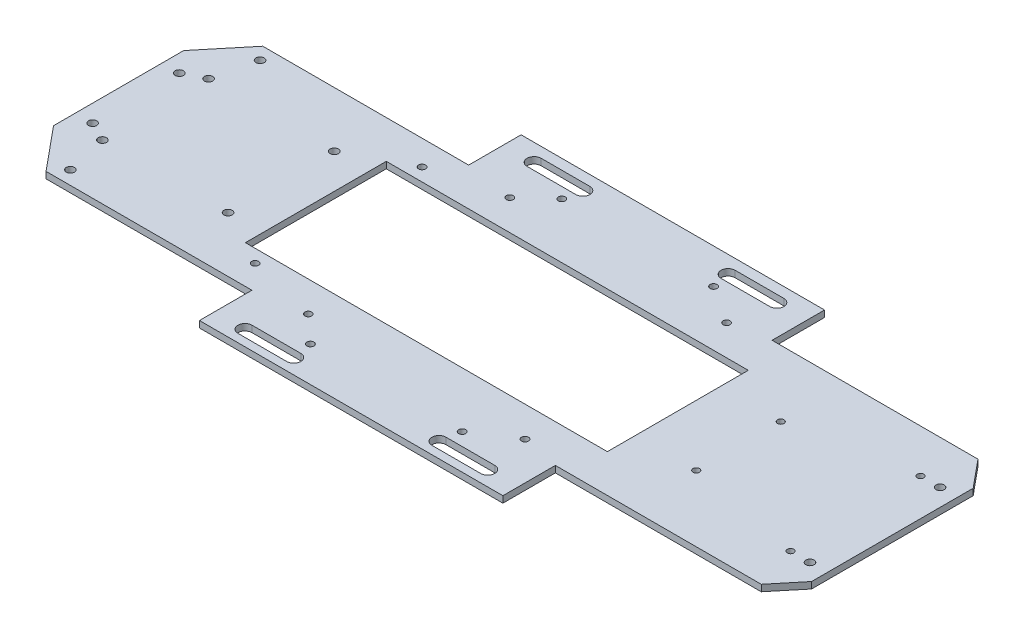
SolidWorks part; units mm, degrees
material "Perspex (TM) GS Acrylic Cast Sheet"
ref_plane "Front Plane" through (0, 0, 0) normal (0, 0, 1) x (1, 0, 0)
ref_plane "Top Plane" through (0, 0, 0) normal (0, 1, 0) x (1, 0, 0)
ref_plane "Right Plane" through (0, 0, 0) normal (1, 0, 0) x (0, 0, -1)
sketch "Sketch1" plane through (0, 0, 0) normal (0, 1, 0) x (1, 0, 0)
  line L0 (181.5, -30) -> (165, -50)
  line L1 (-165, -50) -> (-70, -50)
  line L3 (-165, 50) -> (-70, 50)
  line L4 (181.5, -30) -> (181.5, 30)
  line L5 (-181.5, 0) -> (181.5, 0) construction
  line L6 (0, 50) -> (0, -50) construction
  line L7 (181.5, 30) -> (165, 50)
  line L8 (-165, 50) -> (-181.5, 30)
  line L9 (-181.5, 30) -> (-181.5, -30)
  line L10 (-181.5, -30) -> (-165, -50)
  line L11 (70, 50) -> (165, 50)
  line L13 (-70, 50) -> (-70, 74.2)
  line L14 (-70, 74.2) -> (70, 74.2)
  line L15 (70, 50) -> (70, 74.2)
  line L17 (-70, -50) -> (-70, -74.2)
  line L18 (-70, -74.2) -> (70, -74.2)
  line L19 (70, -50) -> (70, -74.2)
  line L20 (70, -50) -> (165, -50)
  line L21 (0, 74.2) -> (0, -74.2) construction
  line L22 (-90.5, 32.5) -> (76.5, 32.5)
  line L23 (-90.5, 32.5) -> (-90.5, -32.5)
  line L24 (-90.5, -32.5) -> (76.5, -32.5)
  line L25 (76.5, 32.5) -> (76.5, -32.5)
  line L26 (-70, 58) -> (70, 58) construction
  line L27 (-47.5, 46.5) -> (52.5, 46.5) construction
  line L28 (-47.5, -46.5) -> (52.5, -46.5) construction
  circle A0 centre (-35, -58) radius 1.6
  circle A2 centre (-35, 58) radius 1.6
  circle A3 centre (35, 58) radius 1.6
  circle A4 centre (35, -58) radius 1.6
  circle A5 centre (-80, 38.5) radius 1.6
  circle A6 centre (-80, -38.5) radius 1.6
  circle A7 centre (-47.5, 46.5) radius 1.6
  circle A8 centre (52.5, 46.5) radius 1.6
  circle A9 centre (52.5, -46.5) radius 1.6
  circle A10 centre (-47.5, -46.5) radius 1.6
  point P0 (0, 0)
  point P16 (0, 0)
  point P27 (76.5, 0)
  point P33 (0, 58)
  point P36 (0, -62.18)
  dimension "D15" = 3.2
  dimension "D16" = 3.2
  dimension "D21" = 3.2
  dimension "D22" = 3.2
  dimension "D26" = 3.2
  dimension "D27" = 3.2
  dimension "D30" = 3.2
  dimension "D1" = 100
  dimension "D3" = 16.5
  dimension "D2" = 363
  dimension "D5" = 20
  dimension "D6" = 20
  dimension "D4" = 330
  dimension "D7" = 140
  dimension "D8" = 24.2
  dimension "D10" = 65
  dimension "D11" = 167
  dimension "D9" = 111.5
  dimension "D12" = 16.2
  dimension "D13" = 35
  dimension "D14" = 35
  dimension "D17" = 16.2
  dimension "D19" = 35
  dimension "D18" = 35
  dimension "D20" = 16.2
  dimension "D23" = 105
  dimension "D24" = 6
  dimension "D25" = 10
  dimension "D28" = 6
  dimension "D29" = 10
  dimension "D31" = 100
  dimension "D33" = 14
  dimension "D32" = 17.5
  dimension "D34" = 14
extrude "Boss-Extrude1" add sketch "Sketch1" along normal blind 3
sketch "Sketch2" plane through (0, 3, 0) normal (0, 1, 0) x (1, 0, 0)
  line L0 (167.5, 33.6905) -> (167.5, -33.6905) construction
  line L1 (-173.5, 39.697) -> (-173.5, -39.697) construction
  line L2 (-165, 50) -> (-181.5, 30) construction
  line L3 (-181.5, -30) -> (-165, -50) construction
  line L4 (-181.5, 30) -> (-181.5, -30) construction
  line L5 (-181.5, 0) -> (-130.6097, 0) construction
  line L6 (181.5, 0) -> (113.8591, 0) construction
  line L7 (181.5, -30) -> (181.5, 30) construction
  line L9 (189.1707, 43.7461) -> (175.5, 43.7461)
  line L10 (189.1707, 43.7461) -> (189.1707, -52.4953)
  line L11 (189.1707, -52.4953) -> (175.5, -52.4953)
  line L12 (175.5, 43.7461) -> (175.5, -52.4953)
  circle A0 centre (167.5, -30) radius 1.9
  circle A1 centre (167.5, 30) radius 1.9
  circle A3 centre (-173.5, 20) radius 1.9
  circle A4 centre (-173.5, -20) radius 1.9
  point P8 (167.5, 0)
  dimension "D3" = 3.8
  dimension "D4" = 3.8
  dimension "D5" = 6
  dimension "D10" = 3.8
  dimension "D11" = 3.8
  dimension "D1" = 30
  dimension "D2" = 30
  dimension "D6" = 14
  dimension "D7" = 8
  dimension "D8" = 20
  dimension "D9" = 20
extrude "Cut-Extrude1" cut sketch "Sketch2" against normal through all both and the other way through all
sketch "Sketch3" plane through (0, 3, 0) normal (0, 1, 0) x (1, 0, 0)
  line L0 (-106.5, 24.5) -> (-106.5, -24.5) construction
  line L1 (-164.5, 24.5) -> (-164.5, -24.5) construction
  line L2 (-106.5, 0) -> (-164.5, 0) construction
  line L3 (-70, 50) -> (-165, 50) construction
  line L4 (-181.5, 30) -> (-181.5, -30) construction
  line L5 (-160, 43.75) -> (-160, -43.75) construction
  circle A0 centre (-164.5, 24.5) radius 1.9
  circle A1 centre (-106.5, 24.5) radius 1.9
  circle A2 centre (-106.5, -24.5) radius 1.9
  circle A3 centre (-164.5, -24.5) radius 1.9
  circle A4 centre (-160, 43.75) radius 1.9
  circle A5 centre (-160, -43.75) radius 1.9
  point P18 (-160, 0)
  dimension "D1" = 3.8
  dimension "D8" = 3.8
  dimension "D4" = 58
  dimension "D5" = 49
  dimension "D6" = 50
  dimension "D7" = 17
  dimension "D9" = 87.5
  dimension "D10" = 5
  dimension "D2" = 2
  dimension "D3" = 2
sketch "Sketch7" plane through (0, 3, 0) normal (0, 1, 0) x (1, 0, 0)
  line L0 (0, 0) -> (175.5, 0) construction
  line L2 (175.5, 37.2727) -> (175.5, -37.2727) construction
  line L3 (131.5, 50) -> (131.5, -50) construction
  line L4 (-70, 50) -> (-165, 50) construction
  line L5 (-165, -50) -> (-70, -50) construction
  circle A0 centre (104.5, 19.5) radius 1.5
  circle A1 centre (158.5, 30) radius 1.5
  circle A2 centre (158.5, -30) radius 1.5
  circle A3 centre (104.5, -19.5) radius 1.5
  dimension "D4" = 3
  dimension "D5" = 27
  dimension "D6" = 30
  dimension "D1" = 44
  dimension "D2" = 19.5
  dimension "D3" = 27
extrude "Cut-Extrude4" cut sketch "Sketch3" against normal blind 10
extrude "Cut-Extrude5" cut sketch "Sketch7" against normal blind 10
sketch "Sketch8" plane through (0, 3, 0) normal (0, 1, 0) x (1, 0, 0)
  line L0 (70, 74.2) -> (-70, 74.2) construction
  line L4 (-70, -74.2) -> (70, -74.2) construction
  line L6 (-56, -67.2) -> (-33.5, -67.2) construction
  line L7 (-56, -63.95) -> (-33.5, -63.95)
  line L8 (-56, -70.45) -> (-33.5, -70.45)
  line L9 (33.5, -67.2) -> (56, -67.2) construction
  line L10 (33.5, -63.95) -> (56, -63.95)
  line L11 (33.5, -70.45) -> (56, -70.45)
  line L12 (-56, 66.2) -> (-33.5, 66.2) construction
  line L13 (-56, 69.45) -> (-33.5, 69.45)
  line L14 (-56, 62.95) -> (-33.5, 62.95)
  line L15 (33.5, 66.2) -> (56, 66.2) construction
  line L16 (33.5, 69.45) -> (56, 69.45)
  line L17 (33.5, 62.95) -> (56, 62.95)
  line L18 (-39.6312, 69.45) -> (-39.6312, 62.95) construction
  line L19 (-33.5, -63.95) -> (-33.5, -70.45) construction
  line L20 (-70, 74.2) -> (-70, 50) construction
  line L21 (70, 50) -> (70, 74.2) construction
  arc A0 (-56, -63.95) -> (-56, -70.45) centre (-56, -67.2) ccw
  arc A1 (-33.5, -70.45) -> (-33.5, -63.95) centre (-33.5, -67.2) ccw
  arc A2 (33.5, -63.95) -> (33.5, -70.45) centre (33.5, -67.2) ccw
  arc A3 (56, -70.45) -> (56, -63.95) centre (56, -67.2) ccw
  arc A4 (-56, 69.45) -> (-56, 62.95) centre (-56, 66.2) ccw
  arc A5 (-33.5, 62.95) -> (-33.5, 69.45) centre (-33.5, 66.2) ccw
  arc A6 (33.5, 69.45) -> (33.5, 62.95) centre (33.5, 66.2) ccw
  arc A7 (56, 62.95) -> (56, 69.45) centre (56, 66.2) ccw
  point P14 (-44.75, -67.2)
  point P21 (44.75, -67.2)
  point P26 (-44.75, 66.2)
  point P33 (44.75, 66.2)
  dimension "D1" = 8
  dimension "D2" = 7
  dimension "D3" = 6.5
  dimension "D4" = 14
  dimension "D5" = 14
  dimension "D6" = 22.5
extrude "Stand mount holes" cut sketch "Sketch8" against normal through all
equation "\"width\"=100"
equation "\"D1@Sketch1\"=\"width\""
equation "\"D6@Sketch3\"=\"width\"/2"
equation "\"length\"=363"
equation "\"D2@Sketch1\"=\"length\""
equation "\"centre\"=50"
